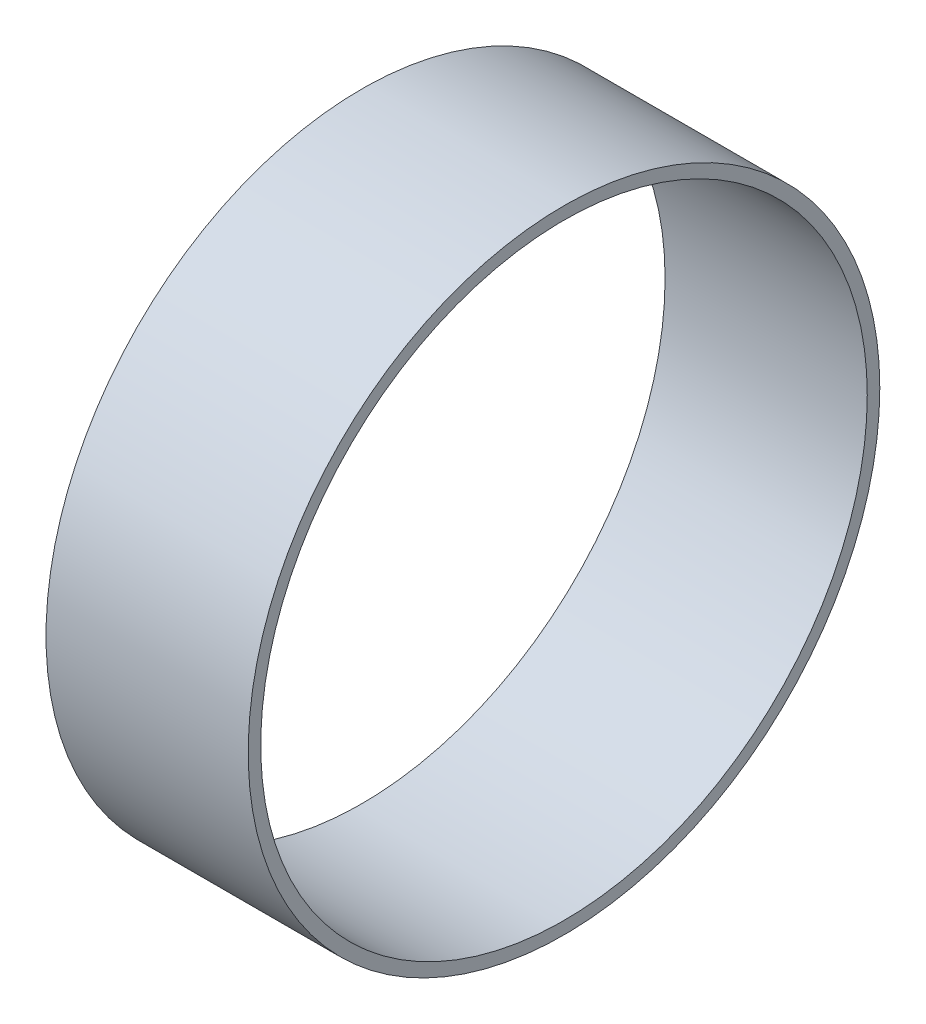
SolidWorks part; units mm, degrees
ref_plane "Front Plane" through (0, 0, 0) normal (0, 0, 1) x (1, 0, 0)
ref_plane "Top Plane" through (0, 0, 0) normal (0, 1, 0) x (1, 0, 0)
ref_plane "Right Plane" through (0, 0, 0) normal (1, 0, 0) x (0, 0, -1)
sketch "Sketch1" plane through (0, 0, 0) normal (1, 0, 0) x (0, 0, -1)
  circle A0 centre (0, 0) radius 39.6748
  circle A2 centre (0, 0) radius 38.1
  dimension "D1" = 79.3496
  dimension "D2" = 76.2
extrude "Boss-Extrude1" add sketch "Sketch1" along normal blind 25.4
